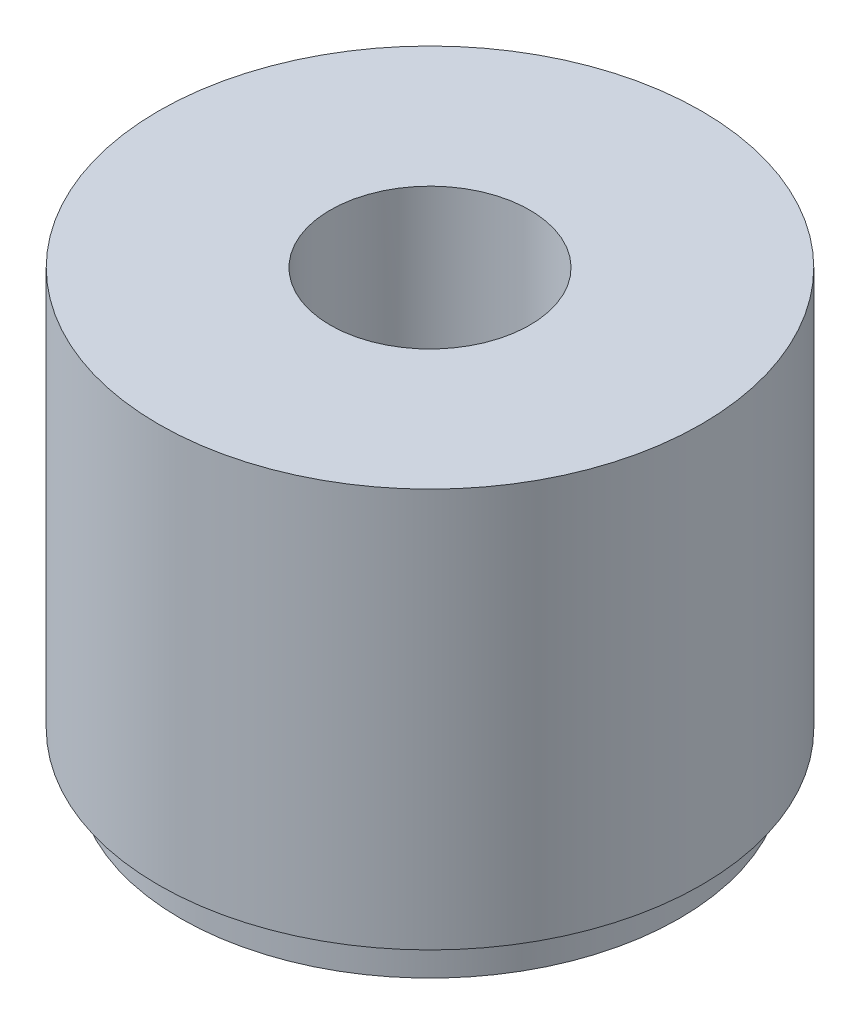
SolidWorks part; units mm, degrees
ref_plane "Front Plane" through (0, 0, 0) normal (0, 0, 1) x (1, 0, 0)
ref_plane "Top Plane" through (0, 0, 0) normal (0, 1, 0) x (1, 0, 0)
ref_plane "Right Plane" through (0, 0, 0) normal (1, 0, 0) x (0, 0, -1)
sketch "Эскиз2" plane through (0, -0.5316, 0) normal (0, -1, 0) x (1, 0, 0)
  circle A0 centre (-0.9202, 0.2116) radius 6.25 construction
  circle A1 centre (-0.9202, 0.2116) radius 6.25
  circle A2 centre (-0.9202, 0.2116) radius 2.5
  circle A3 centre (-0.9202, 0.2116) radius 2.5 construction
extrude "Бобышка-Вытянуть1" add sketch "Эскиз2" along normal blind 1
sketch "Эскиз3" plane through (0, -0.5316, 0) normal (0, 1, 0) x (1, 0, 0)
  circle A0 centre (-0.9202, -0.2116) radius 2.5 construction
  circle A1 centre (-0.9202, -0.2116) radius 2.5
  circle A2 centre (-0.9202, -0.2116) radius 6.8
  dimension "D1" = 13.6
extrude "Бобышка-Вытянуть2" add sketch "Эскиз3" along normal blind 10
